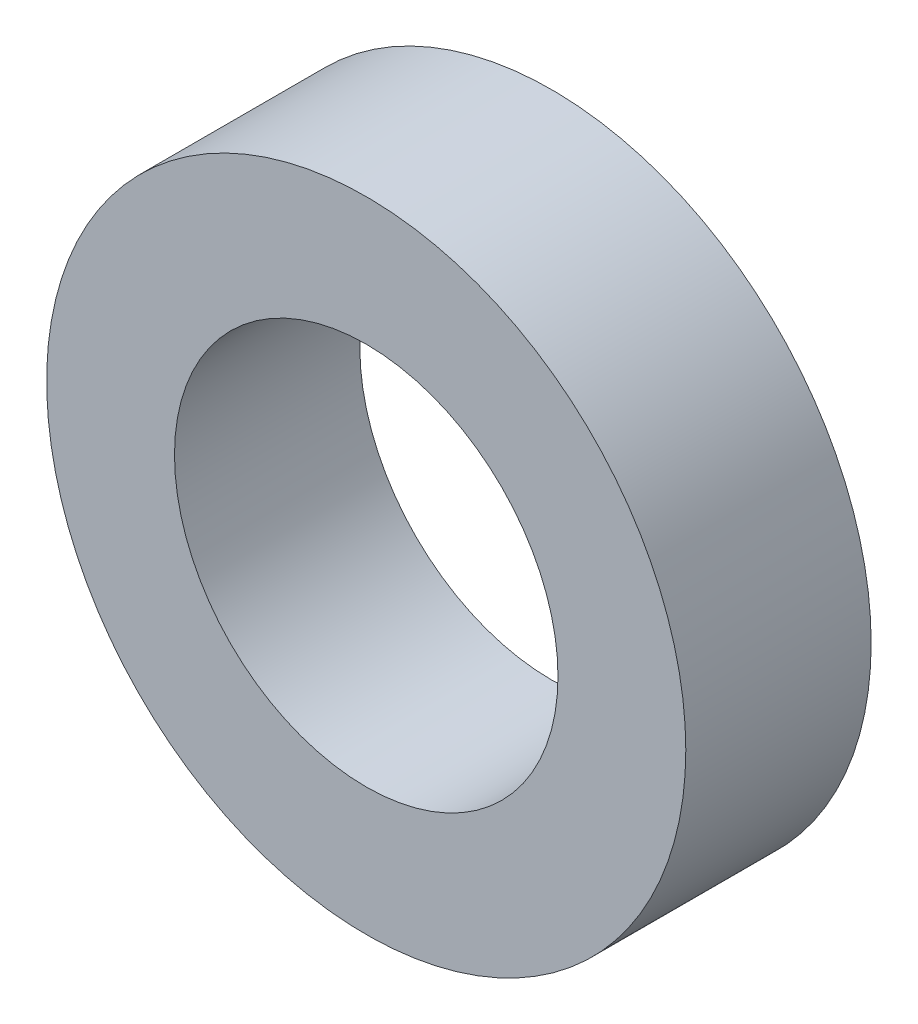
SolidWorks part; units mm, degrees
ref_plane "Front Plane" through (0, 0, 0) normal (0, 0, 1) x (1, 0, 0)
ref_plane "Top Plane" through (0, 0, 0) normal (0, 1, 0) x (1, 0, 0)
ref_plane "Right Plane" through (0, 0, 0) normal (1, 0, 0) x (0, 0, -1)
sketch "Sketch1" plane through (0, 0, 0) normal (0, 0, 1) x (1, 0, 0)
  circle A0 centre (0, 0) radius 3
  circle A1 centre (0, 0) radius 5
  dimension "D1" = 6
  dimension "D2" = 10
extrude "Boss-Extrude1" add sketch "Sketch1" along normal blind 2.9
equation "\"smallPulleyTeeth\"= 15"
equation "\"largePulleyTeeth\"= 30"
equation "\"eighthThick\"= 2.9mm"
equation "\"sixteenthThick\"= 1.7mm"
equation "\"quarterThick\"=5.9mm"
equation "\"OD\"= 145mm"
equation "\"puckAngle\"= 60.5deg"
equation "\"puckDiam\"= 76.5mm"
equation "\"axlePress\"= 5.9mm"
equation "\"press\"= 0.2mm"
equation "\"wheelClear\"= 0.3mm"
equation "\"10-32clear\"= 4.5mm"
equation "\"6-32clear\"= 3.3mm"
equation "\"8-32clear\"= 4.0mm"
equation "\"D1@Boss-Extrude1\"=\"eighthThick\""
